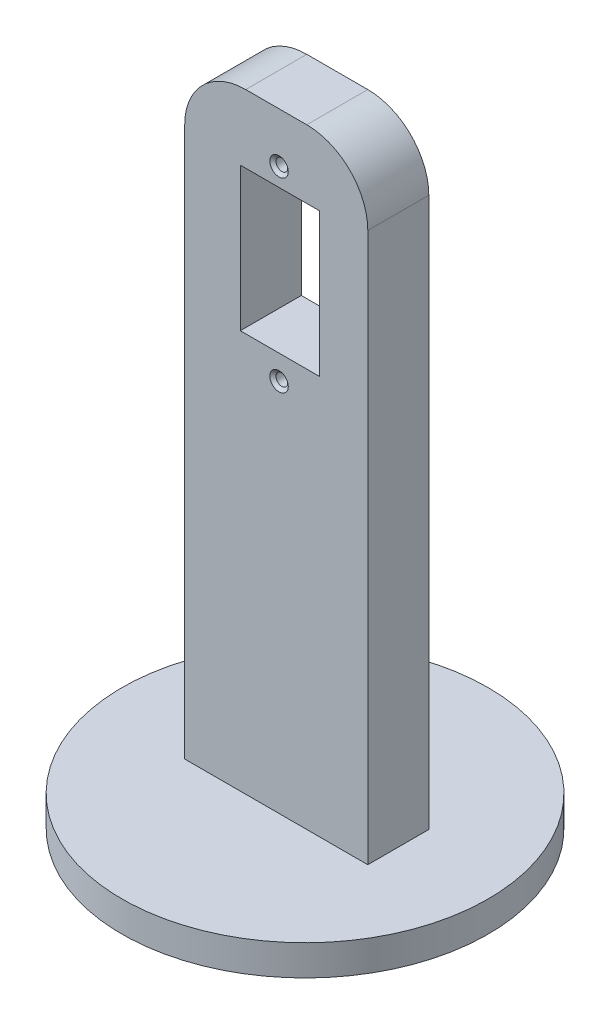
SolidWorks part; units mm, degrees
ref_plane "Front Plane" through (0, 0, 0) normal (0, 0, 1) x (1, 0, 0)
ref_plane "Top Plane" through (0, 0, 0) normal (0, 1, 0) x (1, 0, 0)
ref_plane "Right Plane" through (0, 0, 0) normal (1, 0, 0) x (0, 0, -1)
sketch "Sketch4" plane through (0, 0, 0) normal (0, 0, 1) x (1, 0, 0)
  line L8 (39.6773, 80.317) -> (49.6773, 80.317)
  line L9 (29.6773, 70.317) -> (29.6773, -19.683)
  line L10 (29.6773, -19.683) -> (59.6773, -19.683)
  line L11 (59.6773, 70.317) -> (59.6773, -19.683)
  arc A5 (49.6773, 80.317) -> (59.6773, 70.317) centre (49.6773, 70.317) cw
  arc A6 (39.6773, 80.317) -> (29.6773, 70.317) centre (39.6773, 70.317) ccw
  point P7 (59.6773, 80.317)
  dimension "D3" = 10
  dimension "D1" = 100
  dimension "D2" = 30
extrude "Boss-Extrude1" add sketch "Sketch4" along normal blind 10
sketch "Sketch6" plane through (0, 0, 10) normal (0, 0, 1) x (1, 0, 0)
  line L1 (38.7883, 69.1489) -> (51.7883, 69.1489)
  line L2 (38.7883, 69.1489) -> (38.7883, 45.6489)
  line L3 (38.7883, 45.6489) -> (51.7883, 45.6489)
  line L4 (51.7883, 69.1489) -> (51.7883, 45.6489)
  dimension "D1" = 13
  dimension "D2" = 23.5
extrude "Cut-Extrude1" cut sketch "Sketch6" against normal through all
sketch "Sketch7" plane through (0, 0, 10) normal (0, 0, 1) x (1, 0, 0)
  line L0 (38.7883, 45.6489) -> (51.7883, 45.6489) construction
  line L1 (51.7883, 69.1489) -> (38.7883, 69.1489) construction
  circle A0 centre (45.1364, 72.1489) radius 1.51
  circle A1 centre (45.1364, 41.6489) radius 1.51
  dimension "D1" = 3.02
  dimension "D2" = 3
  dimension "D3" = 4
hole_wizard "CSK for #0 Flat Head Machine Screw (100)2" positions "Sketch12" profile "Sketch13" countersink size "#0" standard "ANSI Inch" end condition through all
sketch "Sketch12" plane through (0, 0, 10) normal (0, 0, 1) x (1, 0, 0)
  point P0 (45.1364, 72.1489)
  point P3 (45.1364, 41.6489)
sketch "Sketch13" plane through (45.1364, 72.1489, 10) normal (1, 0, 0) x (0, -1, 0)
  line L0 (0, 0) -> (0, 10)
  line L1 (0, 10) -> (0.9652, 10)
  line L2 (0.9652, 10) -> (0.9652, 0.4582)
  line L3 (0.9652, 0.4582) -> (1.5113, 0)
  line L5 (1.5113, 0) -> (0, 0)
  line L6 (-0.9652, 0.4582) -> (-1.5113, 0) construction
  line L11 (0, -6.35) -> (0, 107.95) construction
  dimension "Thru Hole Dia." = 1.9304
  dimension "Thru Hole Depth" = 10
  dimension "Near C'Sink Dia." = 3.0226
  dimension "Near C'Sink Angle" = 100
sketch "Sketch15" plane through (0, -19.683, 0) normal (0, -1, 0) x (1, 0, 0)
  circle A0 centre (44.3982, 5) radius 30
  dimension "D1" = 60
extrude "Boss-Extrude2" add sketch "Sketch15" along normal blind 5
